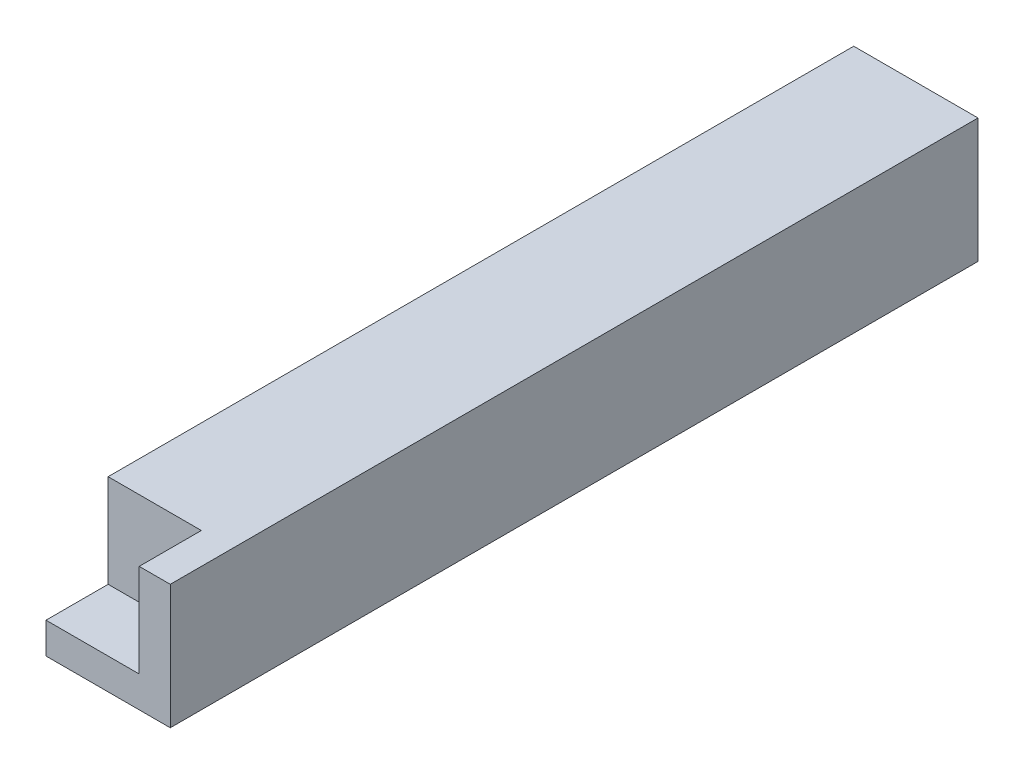
SolidWorks part; units mm, degrees
ref_plane "Front Plane" through (0, 0, 0) normal (0, 0, 1) x (1, 0, 0)
ref_plane "Top Plane" through (0, 0, 0) normal (0, 1, 0) x (1, 0, 0)
ref_plane "Right Plane" through (0, 0, 0) normal (1, 0, 0) x (0, 0, -1)
sketch "Sketch1" plane through (0, 0, 0) normal (0, 0, 1) x (1, 0, 0)
  line L1 (-16.8293, 4.0244) -> (-6.8293, 4.0244)
  line L2 (-16.8293, 4.0244) -> (-16.8293, -5.9756)
  line L3 (-16.8293, -5.9756) -> (-6.8293, -5.9756)
  line L4 (-6.8293, 4.0244) -> (-6.8293, -5.9756)
  dimension "D1" = 10
  dimension "D2" = 10
extrude "Boss-Extrude1" add sketch "Sketch1" along normal blind 65
sketch "Sketch2" plane through (0, 0, 65) normal (0, 0, 1) x (1, 0, 0)
  line L0 (-11.8293, 4.0244) -> (-6.8293, -0.9756)
  line L1 (-6.8293, 4.0244) -> (-16.8293, 4.0244) construction
  line L2 (-6.8293, -5.9756) -> (-6.8293, 4.0244) construction
  line L3 (-6.8293, -0.9756) -> (-11.8293, -5.9756)
  line L4 (-16.8293, -5.9756) -> (-6.8293, -5.9756) construction
  line L5 (-9.3293, -3.4756) -> (-16.8293, -3.4756)
  line L6 (-16.8293, 4.0244) -> (-16.8293, -5.9756) construction
  line L7 (-9.3293, -3.4756) -> (-9.3293, 4.0244)
  line L8 (-16.8293, -3.4756) -> (-16.8293, 4.0244)
  line L9 (-16.8293, 4.0244) -> (-9.3293, 4.0244)
  line M1 (-16.8293, 4.0244) -> (-16.8293, -5.9756)
  line M4 (-6.8293, 4.0244) -> (-16.8293, 4.0244)
extrude "Cut-Extrude1" cut sketch "Sketch2" against normal blind 5 contours L5 L7 L0 M4 M1 | L0 L7 M4
